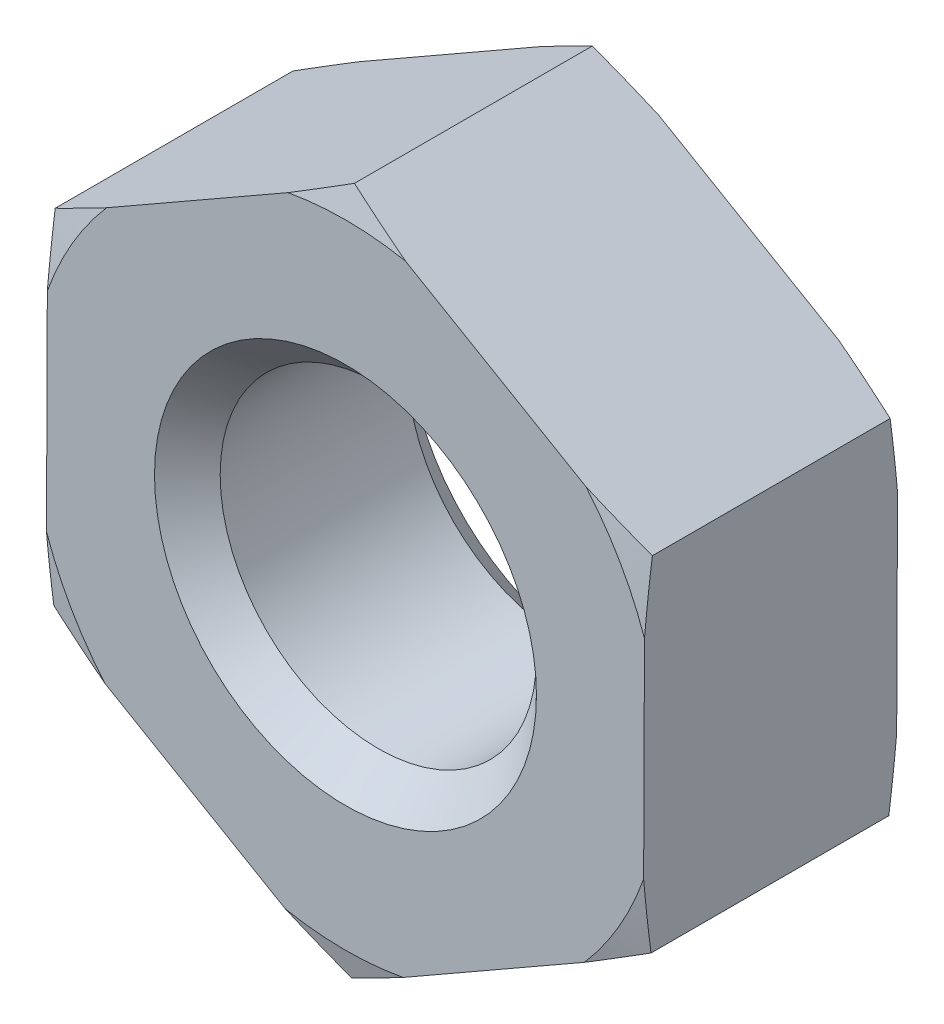
SolidWorks part; units mm, degrees
extrude "基体-拉伸" add sketch "草图1" along normal blind 2
sketch "草图1" plane through (0, 0, 0) normal (0, 0, 1) x (1, 0, 0)
  line L0 (-26.8088, 0) -> (37.1748, 0) construction
  line L1 (0, 25.0215) -> (0, -25.0215) construction
  line L3 (0.0107, 2.725) -> (-2.3545, 1.3718)
  line L4 (-2.3545, 1.3718) -> (-2.3653, -1.3532)
  line L5 (-2.3653, -1.3532) -> (-0.0107, -2.725)
  line L6 (-0.0107, -2.725) -> (2.3545, -1.3718)
  line L7 (2.3545, -1.3718) -> (2.3653, 1.3532)
  line L8 (2.3653, 1.3532) -> (0.0107, 2.725)
  circle A0 centre (0, 0) radius 2.3599 construction
  circle A1 centre (0, 0) radius 1.25
  dimension "D" = 2.5
  dimension "e" = 5.45
cosmetic thread "装饰螺纹线1"
chamfer "倒角1" distance 0.2595 angle 45 2 edges at (1.25, 0, 0) (1.25, 0, 2)
material "AISI 304"
ref_plane "基准面1" through (0, 0, 0) normal (0, 0, 1) x (1, 0, 0)
ref_plane "基准面2" through (0, 0, 0) normal (0, 1, 0) x (1, 0, 0)
ref_plane "基准面3" through (0, 0, 0) normal (1, 0, 0) x (0, 0, -1)
sketch "尺寸草图" plane through (0, 0, 0) normal (0, 0, 1) x (1, 0, 0)
  line L0 (0, 0) -> (34.5249, 0)
  line L1 (34.5249, 0) -> (37.4249, 0)
  line L2 (37.4249, 0) -> (41.5249, 0)
  line L3 (-2.381, 0) -> (0, 0)
  point P3 (2.5, 0)
  point P4 (1.5, 0)
  point P5 (5.45, 0)
  point P6 (2, 0)
  point P7 (6.4, 0)
  point P8 (5, 0)
  dimension "D" = 2.5
  dimension "e" = 5.45
  dimension "P" = 1.5
  dimension "m" = 2
  dimension "mw" = 6.4
  dimension "s" = 5
  dimension "da" = 2.9
  dimension "dw" = 4.1
  dimension "D1" = 2.381
sketch "草图2" plane through (0, 0, 0) normal (0, 0, -1) x (-1, 0, 0)
  circle A0 centre (0, 0) radius 2.5
  circle A1 centre (0, 0) radius 1.25 construction
  dimension "s" = 5
extrude "切除-拉伸1" cut sketch "草图2" against normal through all draft 75 flip side to cut
sketch "草图3" plane through (0, 0, 2) normal (0, 0, 1) x (1, 0, 0)
  circle A0 centre (0, 0) radius 2.5
  dimension "D1" = 5
extrude "切除-拉伸2" cut sketch "草图3" against normal through all draft 75 flip side to cut
equation "\"e@草图1\" = \"e@尺寸草图\""
equation "\"D1@尺寸草图\" = \"D@尺寸草图\" / 1.05"
equation "\"D@草图1\" = \"D@尺寸草图\""
equation "\"m@基体-拉伸\" = \"m@尺寸草图\""
equation "\"D1@草图3\" = \"s@尺寸草图\""
equation "\"s@草图2\" = \"s@尺寸草图\""
equation "\"D2@装饰螺纹线1\" =\"D@尺寸草图\""
equation "\"D1@倒角1\" =  ( \"da@尺寸草图\" - \"D1@尺寸草图\" )  / 2"
